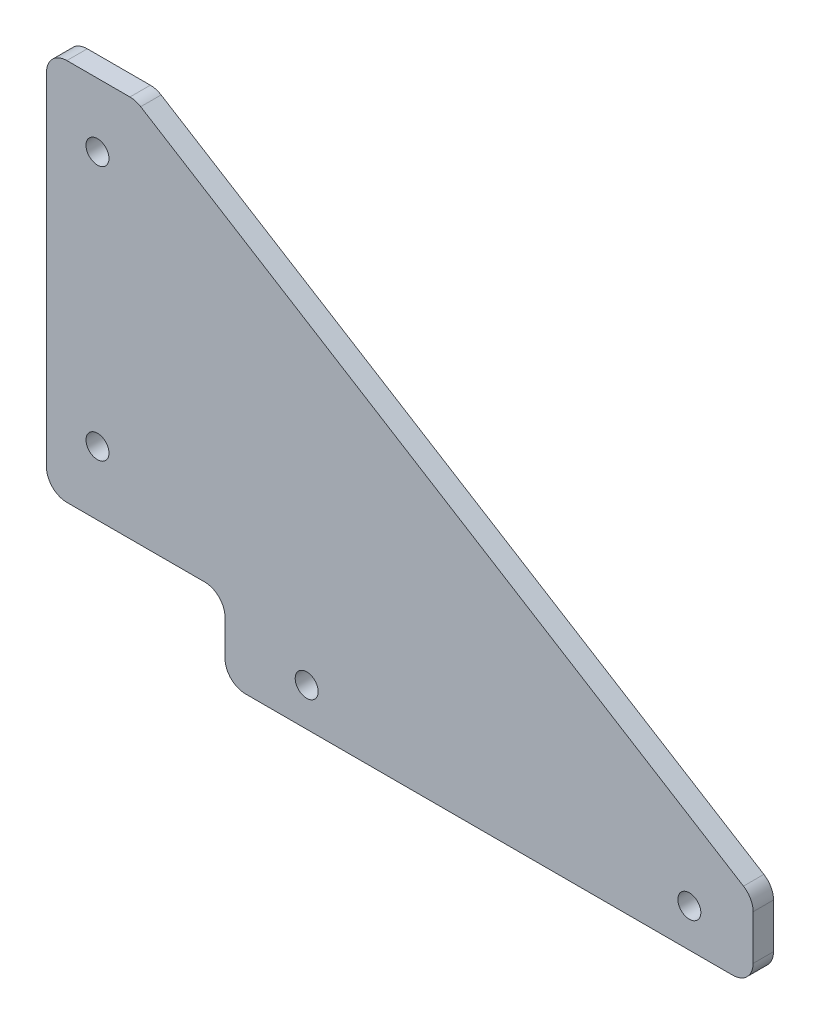
SolidWorks part; units mm, degrees
material "ASTM A36 Steel"
ref_plane "Front Plane" through (0, 0, 0) normal (0, 0, 1) x (1, 0, 0)
ref_plane "Top Plane" through (0, 0, 0) normal (0, 1, 0) x (1, 0, 0)
ref_plane "Right Plane" through (0, 0, 0) normal (1, 0, 0) x (0, 0, -1)
sketch "Sketch1" plane through (0, 0, 0) normal (0, 0, 1) x (1, 0, 0)
  line L0 (-119.3907, 123.2517) -> (-119.3907, -10.7483)
  line L1 (-111.3907, -18.7483) -> (-57.3907, -18.7483)
  line L2 (-49.3907, -26.7483) -> (-49.3907, -40.7483)
  line L3 (-41.3907, -48.7483) -> (149.6093, -48.7483)
  line L4 (157.6093, -40.7483) -> (157.6093, -23.2018)
  line L5 (153.824, -16.402) -> (-82.4542, 130.0514)
  line L6 (-86.6689, 131.2517) -> (-111.3907, 131.2517)
  arc A0 (-86.6689, 131.2517) -> (-82.4542, 130.0514) centre (-86.6689, 123.2517) cw
  arc A1 (153.824, -16.402) -> (157.6093, -23.2018) centre (149.6093, -23.2018) cw
  arc A2 (157.6093, -40.7483) -> (149.6093, -48.7483) centre (149.6093, -40.7483) cw
  arc A3 (-41.3907, -48.7483) -> (-49.3907, -40.7483) centre (-41.3907, -40.7483) cw
  arc A4 (-49.3907, -26.7483) -> (-57.3907, -18.7483) centre (-57.3907, -26.7483) ccw
  arc A5 (-111.3907, -18.7483) -> (-119.3907, -10.7483) centre (-111.3907, -10.7483) cw
  arc A6 (-119.3907, 123.2517) -> (-111.3907, 131.2517) centre (-111.3907, 123.2517) cw
  circle A7 centre (-99.3907, 106.2517) radius 4.5
  circle A8 centre (-99.3907, 6.2517) radius 4.5
  circle A9 centre (-17.3907, -33.7483) radius 4.5
  circle A10 centre (132.6093, -33.7483) radius 4.5
  point P9 (-84.3907, 131.2517)
  point P12 (157.6093, -18.7483)
  point P15 (157.6093, -48.7483)
  point P18 (-49.3907, -48.7483)
  point P21 (-49.3907, -18.7483)
  point P24 (-119.3907, -18.7483)
  point P27 (-119.3907, 131.2517)
  dimension "D7" = 8
  dimension "D8" = 25
  dimension "D11" = 20
  dimension "D12" = 20
  dimension "D13" = 100
  dimension "D14" = 15
  dimension "D16" = 150
  dimension "D1" = 207
  dimension "D2" = 70
  dimension "D3" = 150
  dimension "D4" = 30
  dimension "D5" = 35
  dimension "D6" = 30
  dimension "D15" = 25
extrude "Boss-Extrude1" add sketch "Sketch1" along normal blind 8
